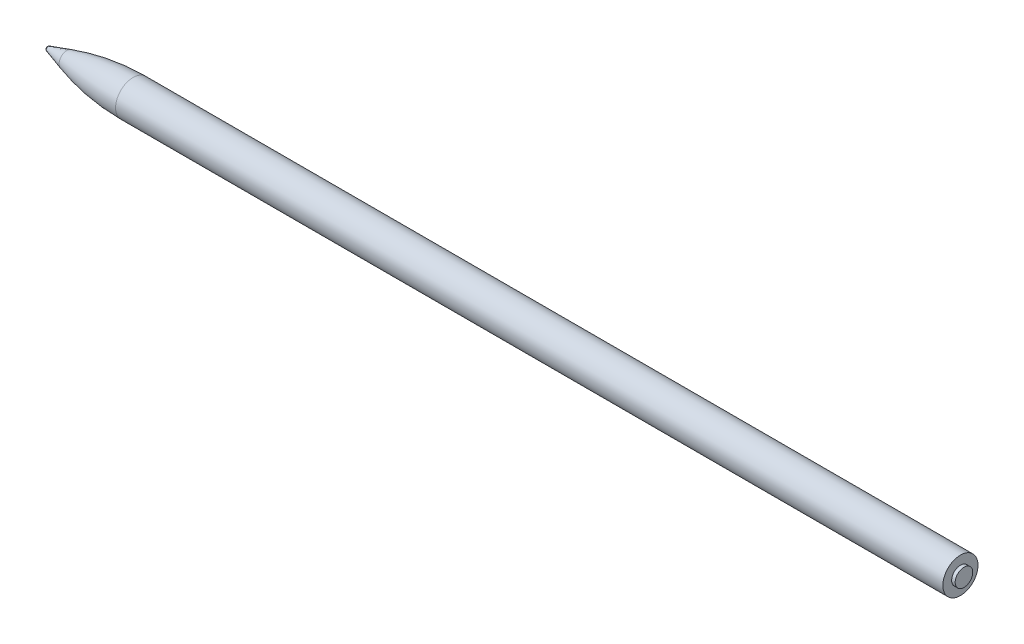
SolidWorks part; units mm, degrees
ref_plane "前视基准面" through (0, 0, 0) normal (0, 0, 1) x (1, 0, 0)
ref_plane "上视基准面" through (0, 0, 0) normal (0, 1, 0) x (1, 0, 0)
ref_plane "右视基准面" through (0, 0, 0) normal (1, 0, 0) x (0, 0, -1)
other "Configuration Table"
sketch "草图1" plane through (0, 0, 0) normal (0, 0, 1) x (1, 0, 0)
  line L0 (0, 0) -> (-52.2, 0) construction
  line L1 (0, 0) -> (0, 0.5)
  line L2 (0, 0.5) -> (-0.2, 0.5)
  line L3 (-0.2, 0.5) -> (-0.2, 1)
  line L4 (-0.2, 1) -> (-47.2937, 1)
  line L5 (-51.07, 0.4394) -> (-52.1078, 0.1244)
  line L6 (0, 0) -> (-52.2, 0)
  arc A0 (-47.2937, 1) -> (-51.07, 0.4394) centre (-47.2937, -12) ccw
  arc A1 (-52.1078, 0.1244) -> (-52.2, 0) centre (-52.07, 0) ccw
  dimension "D4" = 0.13
  dimension "D6" = 13
  dimension "D1" = 52.2
  dimension "D2" = 1
  dimension "D3" = 2
  dimension "D5" = 1
  dimension "D7" = 0.2
revolve "旋转1" add sketch "草图1" angle 360 about L0
